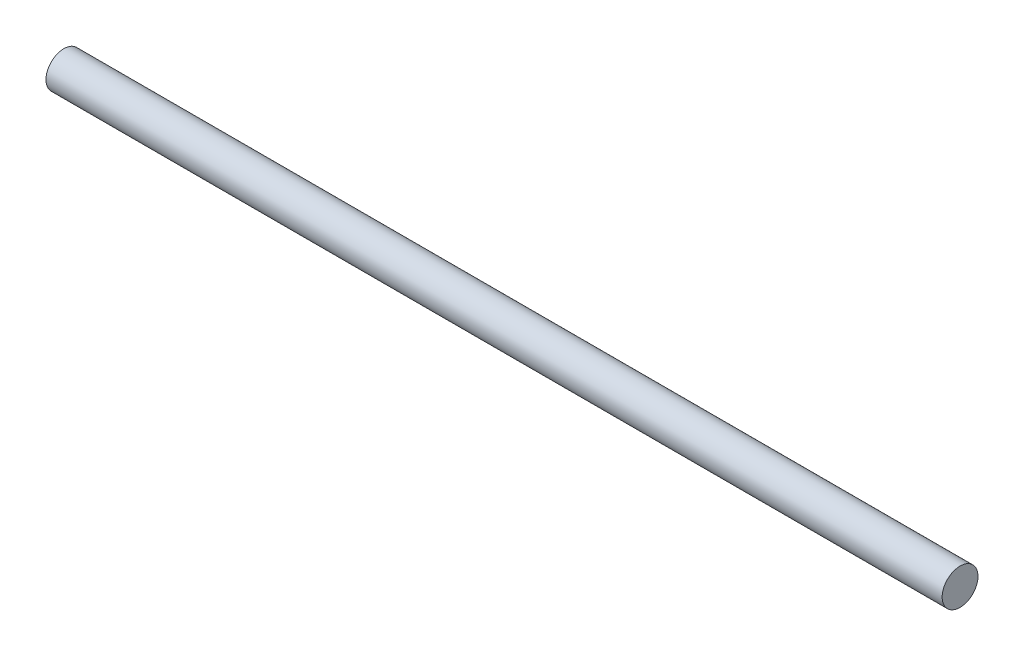
SolidWorks part; units mm, degrees
ref_plane "Front Plane" through (0, 0, 0) normal (0, 0, 1) x (1, 0, 0)
ref_plane "Top Plane" through (0, 0, 0) normal (0, 1, 0) x (1, 0, 0)
ref_plane "Right Plane" through (0, 0, 0) normal (1, 0, 0) x (0, 0, -1)
sketch "Sketch1" plane through (0, 0, 0) normal (1, 0, 0) x (0, 0, -1)
  circle A0 centre (0, 0) radius 3.556
  point P3 (0, 0)
  dimension "D1" = 7.112
extrude "Boss-Extrude1" add sketch "Sketch1" along normal blind 177.8
